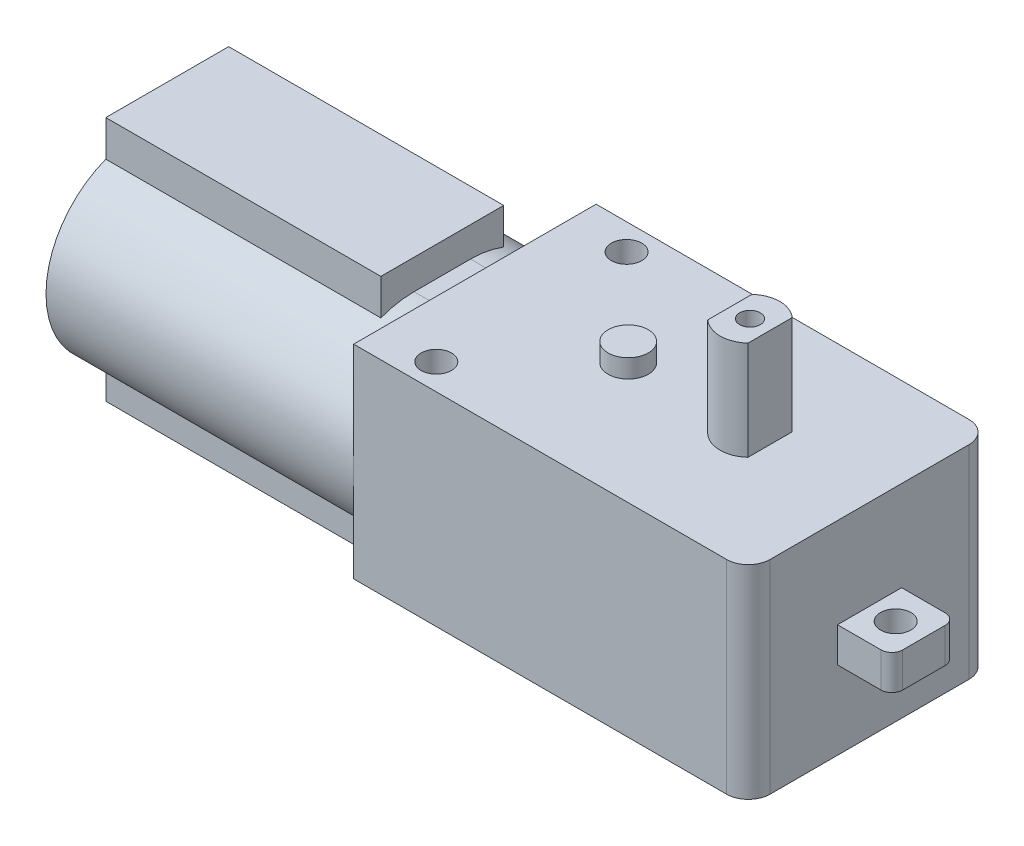
SolidWorks part; units mm, degrees
ref_plane "Front Plane" through (0, 0, 0) normal (0, 0, 1) x (1, 0, 0)
ref_plane "Top Plane" through (0, 0, 0) normal (0, 1, 0) x (1, 0, 0)
ref_plane "Right Plane" through (0, 0, 0) normal (1, 0, 0) x (0, 0, -1)
sketch "Sketch1" plane through (0, 0, 0) normal (0, 1, 0) x (1, 0, 0)
  line L0 (11, 0) -> (-25.3, 0) construction
  line L1 (-25.3, 11.15) -> (9, 11.15)
  line L2 (-25.3, 11.15) -> (-25.3, -11.15)
  line L3 (-25.3, -11.15) -> (9, -11.15)
  line L4 (11, 9.15) -> (11, -9.15)
  line L5 (-20.1, 8.75) -> (-20.1, -8.75) construction
  arc A0 (9, -11.15) -> (11, -9.15) centre (9, -9.15) ccw
  arc A1 (9, 11.15) -> (11, 9.15) centre (9, 9.15) cw
  circle A3 centre (-20.1, 8.75) radius 1.4
  circle A4 centre (-20.1, -8.75) radius 1.4
  point P10 (0, 0)
  point P11 (11, -11.15)
  point P15 (-20.1, 0)
  point P19 (11, 11.15)
  dimension "D1" = 11
  dimension "D8" = 2.8
  dimension "D3" = 22.3
  dimension "D4" = 17.5
  dimension "D5" = 31.1
  dimension "D7" = 36.3
extrude "Boss-Extrude1" add sketch "Sketch1" along normal blind 18.7
sketch "Sketch2" plane through (0, 18.7, 0) normal (0, 1, 0) x (1, 0, 0)
  line L0 (-1.85, 2.0347) -> (-1.85, -2.0347)
  line L1 (1.85, 2.0347) -> (1.85, -2.0347)
  circle A0 centre (0, 0) radius 0.95
  circle A1 centre (0, 0) radius 2.75
  dimension "D1" = 5.5
  dimension "D2" = 1.9
  dimension "D3" = 3.7
extrude "Boss-Extrude2" add sketch "Sketch2" along normal blind 9.1 contours L1 A1 L0 A0
sketch "Sketch3" plane through (0, 18.7, 0) normal (0, 1, 0) x (1, 0, 0)
  line L0 (11, -9.15) -> (11, 9.15) construction
  circle A0 centre (-11.2, 0) radius 1.85
  dimension "D1" = 3.7
  dimension "D2" = 22.2
extrude "Boss-Extrude3" add sketch "Sketch3" along normal blind 1.7
ref_plane "Plane1" through (0, 7.2, 0) normal (0, -1, 0) x (-1, 0, 0)
sketch "Sketch4" plane through (0, 7.2, 0) normal (0, -1, 0) x (-1, 0, 0)
  line L0 (-11, -9.15) -> (-11, 9.15) construction
  line L1 (-11, -2.95) -> (-15, -2.95)
  line L2 (-11, -2.95) -> (-11, 2.95)
  line L3 (-11, 2.95) -> (-15, 2.95)
  line L4 (-16, -1.95) -> (-16, 1.95)
  circle A0 centre (-13.4, 0) radius 1.4
  arc A1 (-15, -2.95) -> (-16, -1.95) centre (-15, -1.95) cw
  arc A2 (-15, 2.95) -> (-16, 1.95) centre (-15, 1.95) ccw
  point P4 (-11, 0)
  point P11 (-16, -2.95)
  point P14 (-16, 2.95)
  dimension "D3" = 2.8
  dimension "D5" = 1
  dimension "D1" = 5
  dimension "D2" = 5.9
  dimension "D4" = 2.4
extrude "Boss-Extrude4" add sketch "Sketch4" against normal blind 3.2
sketch "Sketch5" plane through (-25.3, 0, 0) normal (-1, 0, 0) x (0, 0, 1)
  line L0 (-2.6, 8.55) -> (2.6, 8.55) construction
  line L1 (-2.6, 17.1) -> (2.6, 17.1)
  line L2 (-2.6, 0) -> (2.6, 0)
  line L3 (-11.15, 18.7) -> (-11.15, 0) construction
  line L4 (11.15, 18.7) -> (11.15, 0) construction
  line L5 (-11.15, 0) -> (11.15, 0) construction
  arc A0 (-2.6, 17.1) -> (-2.6, 0) centre (-2.6, 8.55) ccw
  arc A1 (2.6, 0) -> (2.6, 17.1) centre (2.6, 8.55) ccw
  point P2 (0, 8.55)
  point P13 (-11.15, 9.35)
  dimension "D1" = 17.1
extrude "Boss-Extrude5" add sketch "Sketch5" along normal blind 28.3
sketch "Sketch7" plane through (-53.6, 0, 0) normal (-1, 0, 0) x (0, 0, 1)
  line L0 (0, 17.1) -> (0, 0) construction
  line L1 (-5.65, 19.85) -> (5.65, 19.85)
  line L2 (-5.65, 19.85) -> (-5.65, -2.75)
  line L3 (-5.65, -2.75) -> (5.65, -2.75)
  line L4 (5.65, 19.85) -> (5.65, -2.75)
  line L5 (-5.65, 19.85) -> (5.65, -2.75) construction
  line L6 (-5.65, -2.75) -> (5.65, 19.85) construction
  line L7 (2.6, 17.1) -> (-2.6, 17.1) construction
  point P0 (0, 8.55)
  point P18 (0, 8.55)
  dimension "D1" = 22.6
  dimension "D2" = 11.3
extrude "Boss-Extrude6" add sketch "Sketch7" against normal offset from surface (25.3 mm away) 3 up to face at (-25.3, 15.3736, 0)
